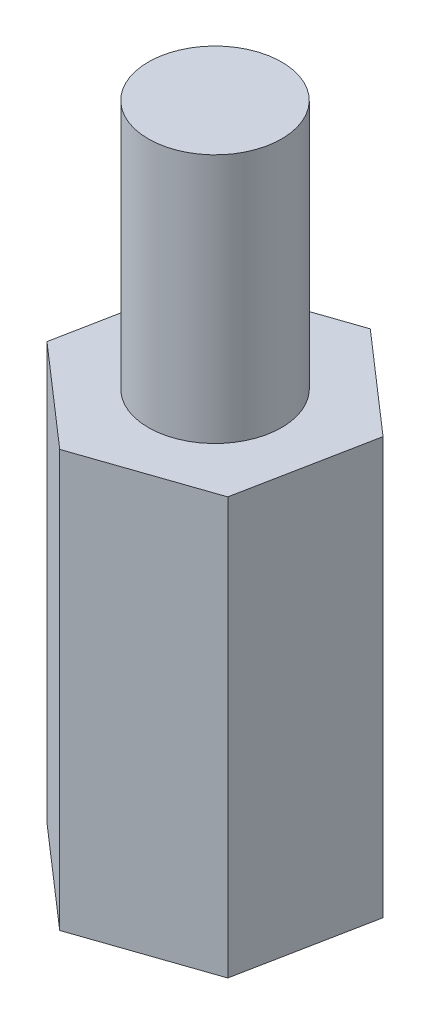
SolidWorks part; units mm, degrees
ref_plane "Front" through (0, 0, 0) normal (0, 0, 1) x (1, 0, 0)
ref_plane "Top" through (0, 0, 0) normal (0, 1, 0) x (1, 0, 0)
ref_plane "Right" through (0, 0, 0) normal (1, 0, 0) x (0, 0, -1)
sketch "Sketch1" plane through (0, 0, 0) normal (0, 1, 0) x (1, 0, 0)
  line L1 (3.004, 1.0292) -> (0.6107, 3.1161)
  line L2 (0.6107, 3.1161) -> (-2.3933, 2.087)
  line L3 (-2.3933, 2.087) -> (-3.004, -1.0292)
  line L4 (-3.004, -1.0292) -> (-0.6107, -3.1161)
  line L5 (-0.6107, -3.1161) -> (2.3933, -2.087)
  line L6 (2.3933, -2.087) -> (3.004, 1.0292)
  circle A0 centre (0, 0) radius 2.75 construction
  circle A1 centre (0, 0) radius 1.5
  dimension "D2" = 3
  dimension "D1" = 5.5
extrude "Boss-Extrude1" add sketch "Sketch1" along normal blind 10
sketch "Sketch2" plane through (0, 10, 0) normal (0, 1, 0) x (1, 0, 0)
  circle A0 centre (0, 0) radius 1.6
  dimension "D1" = 3.2
extrude "Boss-Extrude2" add sketch "Sketch2" along normal blind 6
